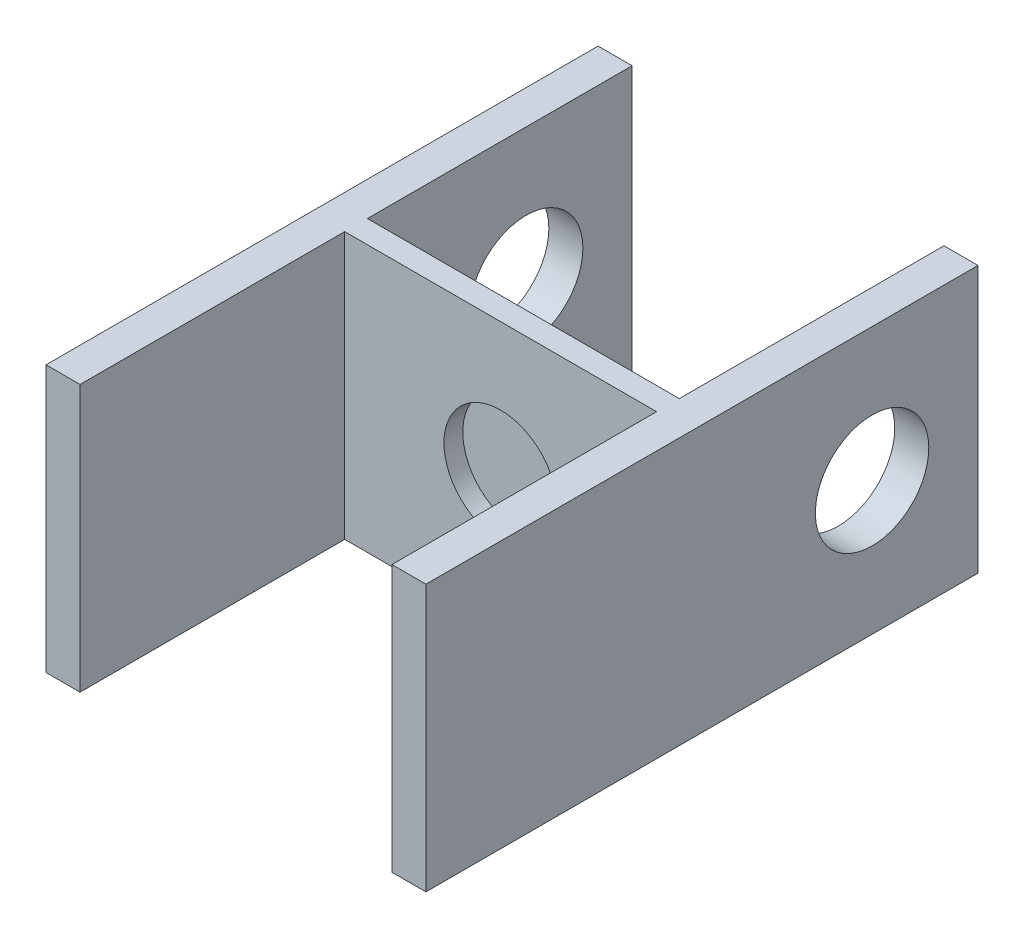
SolidWorks part; units mm, degrees
material "PE High Density"
ref_plane "Front Plane" through (0, 0, 0) normal (0, 0, 1) x (1, 0, 0)
ref_plane "Top Plane" through (0, 0, 0) normal (0, 1, 0) x (1, 0, 0)
ref_plane "Right Plane" through (0, 0, 0) normal (1, 0, 0) x (0, 0, -1)
sketch "Sketch1" plane through (0, 0, 0) normal (0, 1, 0) x (1, 0, 0)
  line L0 (-137.5, -243.4) -> (-167.5, -243.4)
  line L1 (167.5, -243.4) -> (137.5, -243.4)
  line L2 (167.5, -243.4) -> (167.5, 243.4)
  line L3 (167.5, 243.4) -> (137.5, 243.4)
  line L4 (-167.5, -243.4) -> (-167.5, 243.4)
  line L5 (167.5, -243.4) -> (-167.5, 243.4) construction
  line L6 (167.5, 243.4) -> (-167.5, -243.4) construction
  line L8 (-137.5, -243.4) -> (-137.5, -10)
  line L9 (-137.5, -10) -> (137.5, -10)
  line L10 (137.5, -243.4) -> (137.5, -10)
  line L12 (-137.5, 243.4) -> (-137.5, 10)
  line L13 (-137.5, 10) -> (137.5, 10)
  line L14 (137.5, 243.4) -> (137.5, 10)
  line L15 (-137.5, 243.4) -> (-167.5, 243.4)
  point P0 (0, 0)
  dimension "D1" = 275
  dimension "D2" = 233.4
  dimension "D3" = 30
  dimension "D4" = 30
  dimension "D5" = 20
  dimension "D6" = 233.4
extrude "Boss-Extrude2" add sketch "Sketch1" along normal blind 235
sketch "Sketch2" plane through (0, 0, 10) normal (0, 0, 1) x (1, 0, 0)
  circle A0 centre (0, 117.5) radius 50
  dimension "D1" = 100
extrude "Cut-Extrude1" cut sketch "Sketch2" against normal blind 16.6
sketch "Sketch4" plane through (167.5, 0, 0) normal (1, 0, 0) x (0, 0, -1)
  circle A0 centre (150, 117.5) radius 50
  dimension "D1" = 100
  dimension "D2" = 150
extrude "Cut-Extrude2" cut sketch "Sketch4" against normal blind 667.6
scale "Scale1" scale about centroid uniform scaling yes scale factor 0.75
